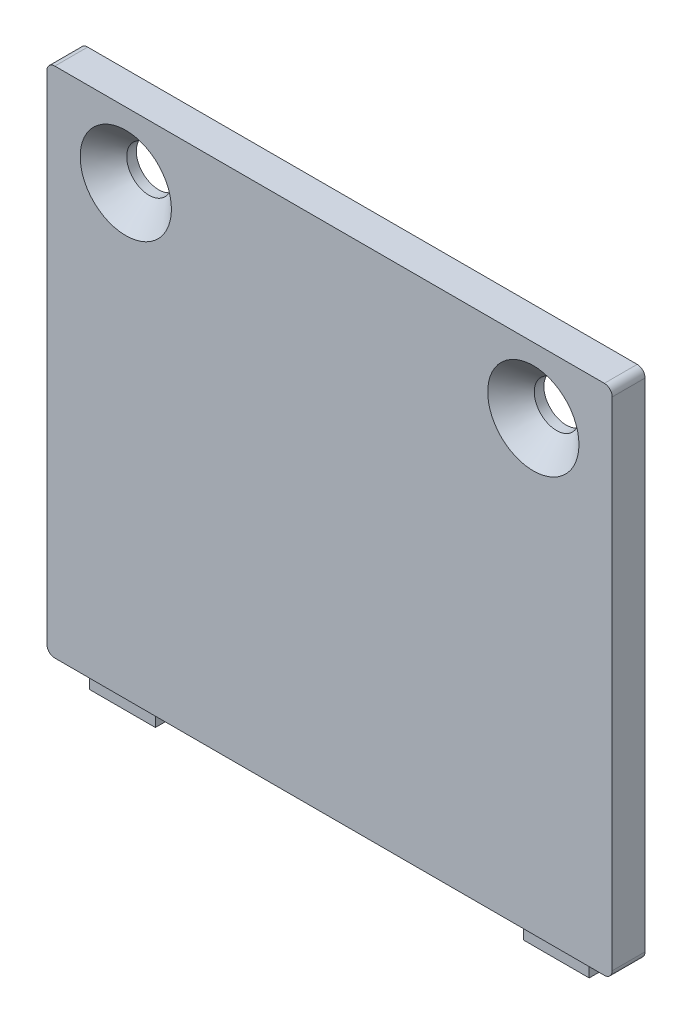
SolidWorks part; units mm, degrees
ref_plane "Alzado" through (0, 0, 0) normal (0, 0, 1) x (1, 0, 0)
ref_plane "Planta" through (0, 0, 0) normal (0, 1, 0) x (1, 0, 0)
ref_plane "Vista lateral" through (0, 0, 0) normal (1, 0, 0) x (0, 0, -1)
sketch "Croquis1" plane through (0, 0, 0) normal (0, 0, 1) x (1, 0, 0)
  line L1 (-21.5, 19.5) -> (21.5, 19.5)
  line L2 (-21.5, 19.5) -> (-21.5, -19.5)
  line L3 (-21.5, -19.5) -> (21.5, -19.5)
  line L4 (21.5, 19.5) -> (21.5, -19.5)
  line L5 (-21.5, 19.5) -> (21.5, -19.5) construction
  line L6 (-21.5, -19.5) -> (21.5, 19.5) construction
  point P0 (0, 0)
  dimension "D1" = 39
  dimension "D2" = 43
extrude "Saliente-Extruir1" add sketch "Croquis1" along normal blind 2.5
sketch "Croquis3" plane through (0, 0, 2.5) normal (0, 0, 1) x (1, 0, 0)
  line L0 (-21.5, 19.5) -> (-21.5, -19.5) construction
  line L1 (21.5, 19.5) -> (-21.5, 19.5) construction
  line L2 (21.5, -19.5) -> (21.5, 19.5) construction
  point P0 (-15.5, 14.5)
  point P6 (15.5, 14.5)
  dimension "D1" = 6
  dimension "D2" = 5
  dimension "D3" = 6
hole_wizard "Avellanado para tornillo con cabeza avellanada de clavija hexagonal de M31" positions "Croquis3D1" profile "Croquis4" countersink size "M3" standard "DIN"
sketch3d "Croquis3D1"
  point P0 (-15.5, 14.5, 2.5)
  point P3 (15.5, 14.5, 2.5)
sketch "Croquis4" plane through (-15.5, 14.5, 2.5) normal (1, 0, 0) x (0, -1, 0)
  line L0 (0, 0) -> (0, 13.0215)
  line L1 (0, 13.0215) -> (1.7, 12)
  line L2 (1.7, 12) -> (1.7, 1.77)
  line L3 (1.7, 1.77) -> (3.47, 0)
  line L5 (3.47, 0) -> (0, 0)
  line L6 (-1.7, 1.77) -> (-3.47, 0) construction
  line L10 (0, 13.0215) -> (-1.7, 12) construction
  line L11 (0, -6.35) -> (0, 107.95) construction
  dimension "Diámetro de taladro" = 3.4
  dimension "Profundidad de taladro" = 12
  dimension "Ángulo de avellanado cercano" = 6.94
  dimension "Ángulo de avellanado lejano" = 90
  dimension "Ángulo de perforador" = 118
sketch "Croquis6" plane through (0, -19.5, 0) normal (0, -1, 0) x (1, 0, 0)
  line L0 (-21.5, 1.25) -> (-16.5, 1.25) construction
  line L1 (-21.5, 2.5) -> (-21.5, 0) construction
  line L2 (0, 0) -> (0, 4.6227) construction
  line L3 (-19, 0.75) -> (-14, 0.75)
  line L4 (-19, 0.75) -> (-19, 1.75)
  line L5 (-19, 1.75) -> (-14, 1.75)
  line L6 (-14, 0.75) -> (-14, 1.75)
  line L7 (-19, 0.75) -> (-14, 1.75) construction
  line L8 (-19, 1.75) -> (-14, 0.75) construction
  line L9 (-21.5, 0) -> (21.5, 0) construction
  line L10 (19, 1.75) -> (14, 1.75)
  line L11 (14, 0.75) -> (14, 1.75)
  line L12 (19, 0.75) -> (14, 0.75)
  line L13 (19, 0.75) -> (19, 1.75)
  dimension "D1" = 5
  dimension "D2" = 5
  dimension "D3" = 1
extrude "Saliente-Extruir2" add sketch "Croquis6" along normal blind 1.5
fillet "Redondeo1" radius 0.6 4 edges at (21.5, -19.5, 1.25) (-21.5, -19.5, 1.25) (-21.5, 19.5, 1.25) (21.5, 19.5, 1.25)
